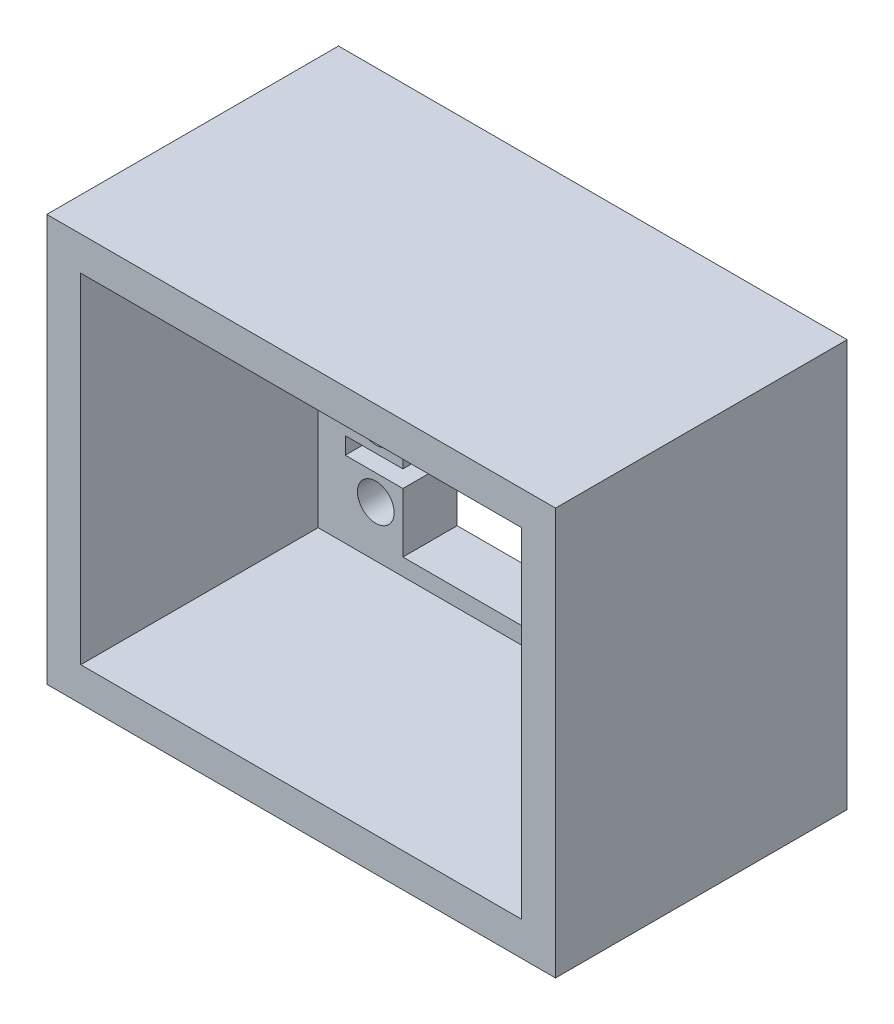
SolidWorks part; units mm, degrees
ref_plane "Front Plane" through (0, 0, 0) normal (0, 0, 1) x (1, 0, 0)
ref_plane "Top Plane" through (0, 0, 0) normal (0, 1, 0) x (1, 0, 0)
ref_plane "Right Plane" through (0, 0, 0) normal (1, 0, 0) x (0, 0, -1)
sketch "Esquisse1" plane through (0, 0, 0) normal (0, 0, 1) x (1, 0, 0)
  line L1 (-37.5, -30) -> (37.5, -30)
  line L2 (-37.5, -30) -> (-37.5, 30)
  line L3 (-37.5, 30) -> (37.5, 30)
  line L4 (37.5, -30) -> (37.5, 30)
  line L5 (-37.5, -30) -> (37.5, 30) construction
  line L6 (-37.5, 30) -> (37.5, -30) construction
  point P0 (0, 0)
  dimension "D1" = 75
  dimension "D2" = 60
extrude "Boss.-Extru.1" add sketch "Esquisse1" against normal blind 8
sketch "Esquisse2" plane through (0, 0, 0) normal (0, 0, 1) x (1, 0, 0)
  line L1 (-20, 22.5) -> (20, 22.5)
  line L2 (-20, 22.5) -> (-20, 2.5)
  line L3 (-20, 2.5) -> (20, 2.5)
  line L4 (20, 22.5) -> (20, 2.5)
  point P4 (0, 22.5)
  dimension "D1" = 40
  dimension "D2" = 20
  dimension "D3" = 2.5
extrude "Enlèv. mat.-Extru.1" cut sketch "Esquisse2" against normal blind 8
sketch "Esquisse3" plane through (0, 0, 0) normal (0, 0, 1) x (1, 0, 0)
  line L0 (-20, 11.25) -> (-28.5, 11.25)
  line L1 (-20, 22.5) -> (-20, 2.5) construction
  line L2 (-28.5, 11.25) -> (-28.5, 13.75)
  line L3 (-28.5, 13.75) -> (-20, 13.75)
  line L4 (-20, 13.75) -> (-20, 11.25)
  line L5 (-20, 12.5) -> (20, 12.5) construction
  line L6 (20, 2.5) -> (20, 22.5) construction
  point P10 (-20, 12.5)
  dimension "D1" = 2.5
  dimension "D2" = 8.5
extrude "Enlèv. mat.-Extru.2" cut sketch "Esquisse3" against normal blind 8
sketch "Esquisse4" plane through (0, 0, 0) normal (0, 0, 1) x (1, 0, 0)
  line L0 (-28.5, 12.5) -> (-4.9147, 12.5) construction
  line L1 (-28.5, 13.75) -> (-28.5, 11.25) construction
  line L2 (-20, 22.5) -> (-20, 13.75) construction
  circle A0 centre (-24, 17.5) radius 2.7
  circle A1 centre (-24, 7.5) radius 2.7
  point P4 (-24.0735, 16.0469)
  point P11 (-24, 5.6485)
  point P12 (-4.9147, 11.0469)
  dimension "D1" = 5.4
  dimension "D2" = 5.4
  dimension "D3" = 10
  dimension "D4" = 5
  dimension "D5" = 4
extrude "Enlèv. mat.-Extru.3" cut sketch "Esquisse4" against normal through all
mirror "Symétrie2" about plane through (0, 0, 0) normal (1, 0, 0) of "Enlèv. mat.-Extru.2", "Enlèv. mat.-Extru.3"
mirror "Symétrie4" about plane through (0, 0, 0) normal (0, 1, 0) of "Symétrie2", "Enlèv. mat.-Extru.2", "Enlèv. mat.-Extru.3", "Enlèv. mat.-Extru.1"
sketch "Esquisse6" plane through (0, 0, 0) normal (0, 0, 1) x (1, 0, 0)
  line L1 (-37.5, 30) -> (37.5, 30)
  line L2 (-37.5, 30) -> (-37.5, -30)
  line L3 (-37.5, -30) -> (37.5, -30)
  line L4 (37.5, 30) -> (37.5, -30)
extrude "Boss.-Extru.2" add sketch "Esquisse6" along normal blind 35
sketch "Esquisse7" plane through (0, 0, 35) normal (0, 0, 1) x (1, 0, 0)
  line L0 (-37.5, 30) -> (-37.5, -30) construction
  line L1 (32.5, -25) -> (-32.5, -25)
  line L2 (32.5, -25) -> (32.5, 25)
  line L3 (32.5, 25) -> (-32.5, 25)
  line L4 (-32.5, -25) -> (-32.5, 25)
  line L5 (32.5, -25) -> (-32.5, 25) construction
  line L6 (32.5, 25) -> (-32.5, -25) construction
  line L7 (37.5, 30) -> (-37.5, 30) construction
  point P0 (0, 0)
  dimension "D1" = 5
  dimension "D2" = 5
extrude "Enlèv. mat.-Extru.4" cut sketch "Esquisse7" against normal blind 35
